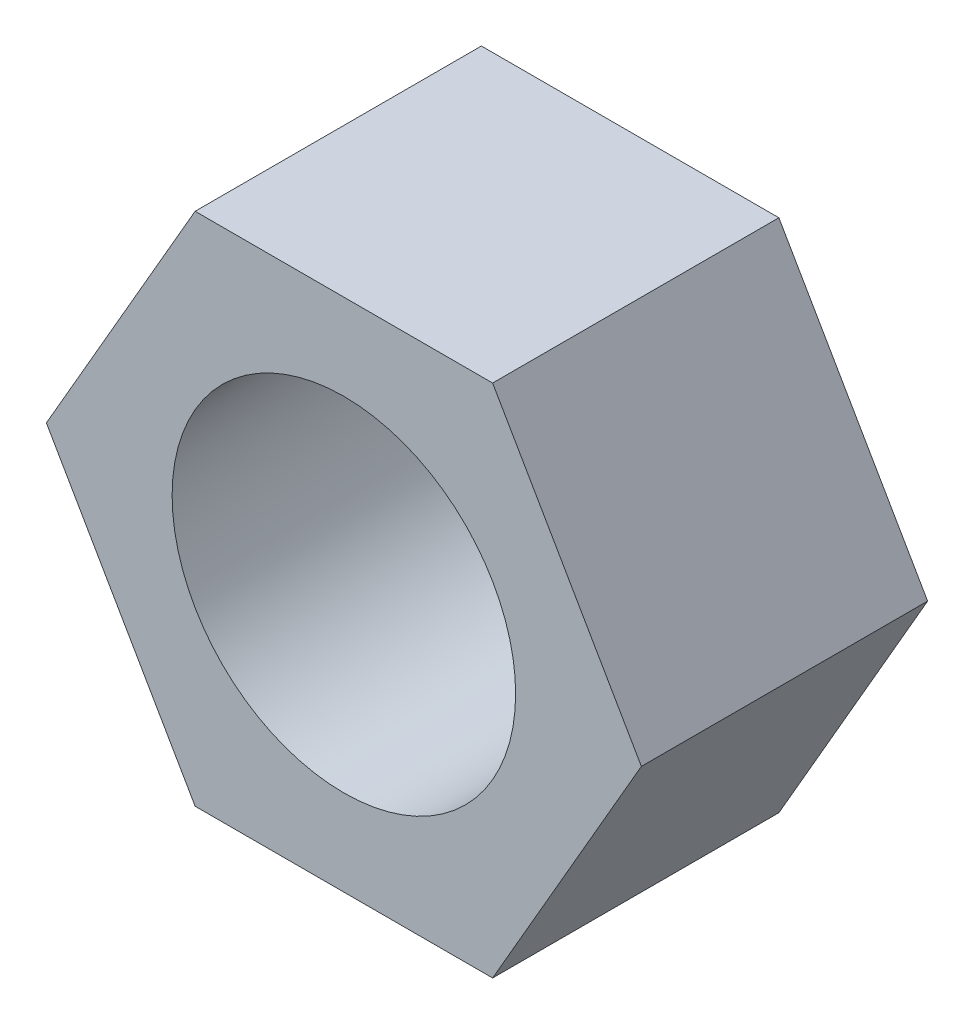
SolidWorks part; units mm, degrees
ref_plane "Front Plane" through (0, 0, 0) normal (0, 0, 1) x (1, 0, 0)
ref_plane "Top Plane" through (0, 0, 0) normal (0, 1, 0) x (1, 0, 0)
ref_plane "Right Plane" through (0, 0, 0) normal (1, 0, 0) x (0, 0, -1)
sketch "Sketch1" plane through (0, 0, 0) normal (0, 0, 1) x (1, 0, 0)
  line L1 (25.9808, 0) -> (12.9904, 22.5)
  line L2 (12.9904, 22.5) -> (-12.9904, 22.5)
  line L3 (-12.9904, 22.5) -> (-25.9808, 0)
  line L4 (-25.9808, 0) -> (-12.9904, -22.5)
  line L5 (-12.9904, -22.5) -> (12.9904, -22.5)
  line L6 (12.9904, -22.5) -> (25.9808, 0)
  circle A0 centre (0, 0) radius 22.5 construction
  circle A1 centre (0, 0) radius 15
  dimension "D1" = 30
  dimension "D2" = 45
extrude "Boss-Extrude1" add sketch "Sketch1" along normal blind 25
